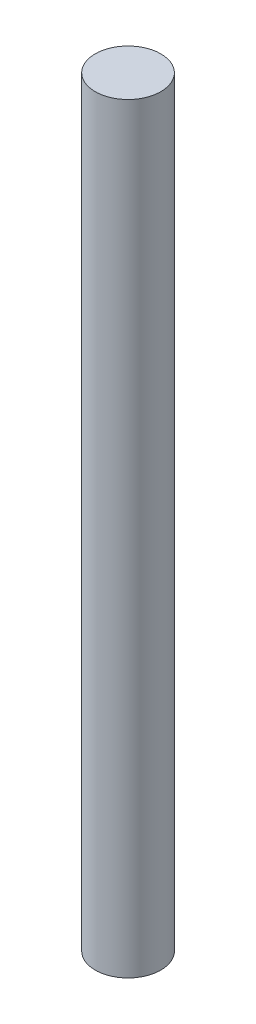
SolidWorks part; units mm, degrees
ref_plane "Front Plane" through (0, 0, 0) normal (0, 0, 1) x (1, 0, 0)
ref_plane "Top Plane" through (0, 0, 0) normal (0, 1, 0) x (1, 0, 0)
ref_plane "Right Plane" through (0, 0, 0) normal (1, 0, 0) x (0, 0, -1)
sketch "Sketch1" plane through (0, 0, 0) normal (0, 1, 0) x (1, 0, 0)
  circle A0 centre (0, 0) radius 2.5
  dimension "D1" = 5
  dimension "D2" = 0
extrude "Boss-Extrude1" add sketch "Sketch1" along normal blind 58
